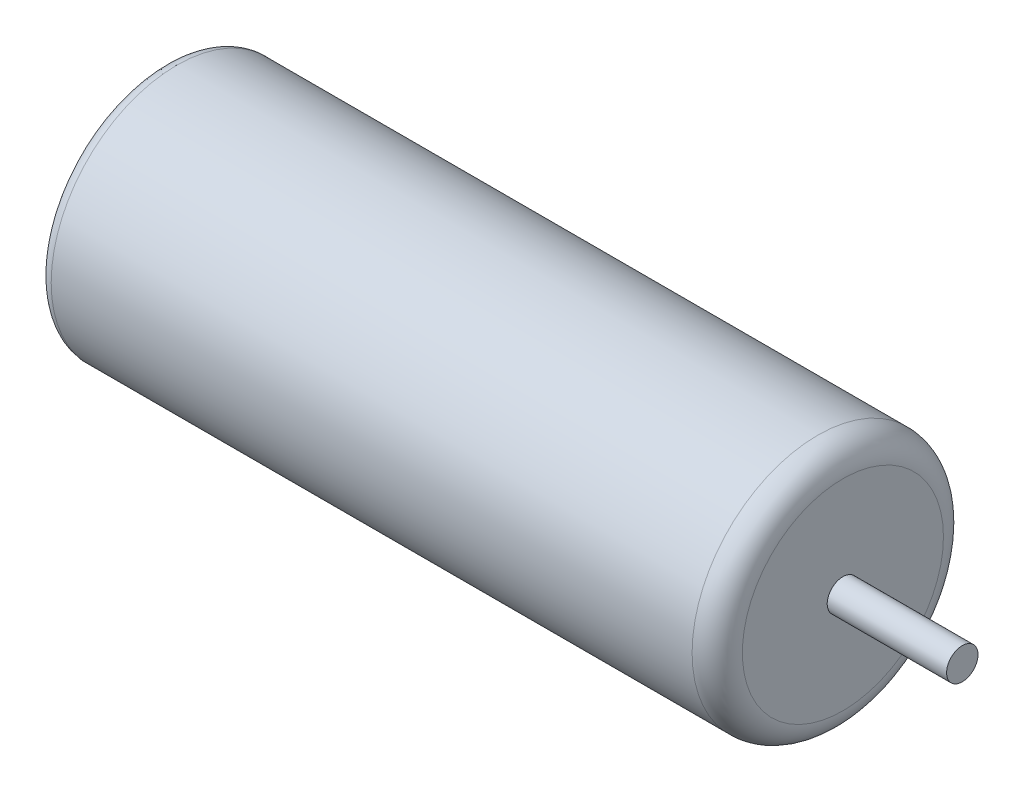
SolidWorks part; units mm, degrees
material "Copper"
ref_plane "Front Plane" through (0, 0, 0) normal (0, 0, 1) x (1, 0, 0)
ref_plane "Top Plane" through (0, 0, 0) normal (0, 1, 0) x (1, 0, 0)
ref_plane "Right Plane" through (0, 0, 0) normal (1, 0, 0) x (0, 0, -1)
sketch "Sketch1" plane through (0, 0, 0) normal (1, 0, 0) x (0, 0, -1)
  circle A0 centre (0, 0) radius 20
extrude "Boss-Extrude1" add sketch "Sketch1" along normal blind 108
sketch "Sketch2" plane through (108, 0, 0) normal (1, 0, 0) x (0, 0, -1)
  circle A0 centre (0, 0) radius 2.5
extrude "Boss-Extrude2" add sketch "Sketch2" along normal blind 19
fillet "Fillet1" radius 2 1 edges at (0, 0, -20)
fillet "Fillet2" radius 4 1 edges at (108, 0, -20)
